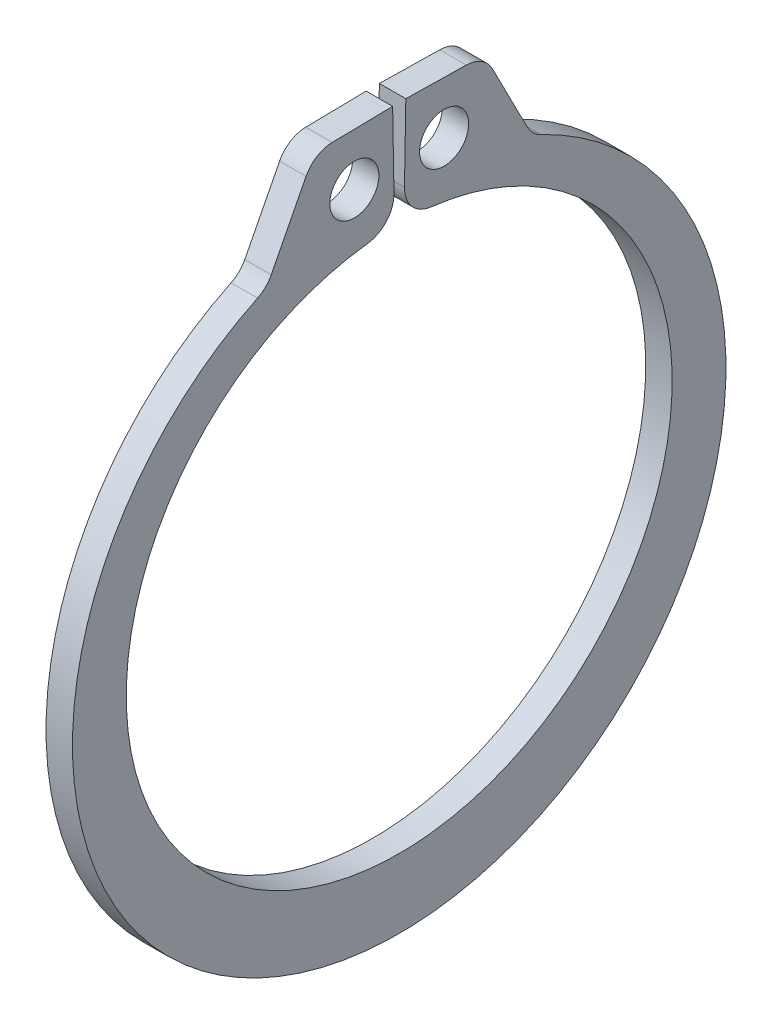
SolidWorks part; units mm, degrees
material "Cast Carbon Steel"
ref_plane "Front" through (0, 0, 0) normal (0, 0, 1) x (1, 0, 0)
ref_plane "Top" through (0, 0, 0) normal (0, 1, 0) x (1, 0, 0)
ref_plane "Right" through (0, 0, 0) normal (1, 0, 0) x (0, 0, -1)
sketch "Sketch1" plane through (0, 0, 0) normal (1, 0, 0) x (0, 0, -1)
  line L0 (0, 0) -> (0, 11.0109) construction
  line L1 (-0.1922, 11.0092) -> (-0.2658, 15.225)
  line L2 (0.2658, 15.225) -> (3.4276, 15.1698)
  line L3 (3.4276, 15.1698) -> (5.3529, 11.4187)
  line L4 (0.1922, 11.0092) -> (0.2658, 15.225)
  line L5 (-0.2658, 15.225) -> (-3.4276, 15.1698)
  line L6 (-3.4276, 15.1698) -> (-5.3529, 11.4187)
  line L7 (-5.3529, 11.4187) -> (-4.6737, 9.9698) construction
  line L8 (5.3529, 11.4187) -> (4.6737, 9.9698) construction
  line L9 (0, -11.0109) -> (0, -13.8049) construction
  line L10 (-3.4276, 15.1698) -> (-0.1922, 11.0092) construction
  line L11 (0, 11.0109) -> (0, 15.2273) construction
  line L12 (-11.0109, 0) -> (11.0109, 0) construction
  circle A0 centre (0, 0) radius 11.0109 construction
  arc A1 (-0.1922, 11.0092) -> (0.1922, 11.0092) centre (0, 0) ccw
  circle A4 centre (-1.8099, 13.0895) radius 0.9906
  circle A5 centre (1.8099, 13.0895) radius 0.9906
  arc A6 (-5.3529, 11.4187) -> (5.3529, 11.4187) centre (0, -0.6251) ccw construction
  point P0 (0, -13.8049)
  dimension "Ring ID" = 22.0218
  dimension "Hole Diameter" = 1.9812
  dimension "Min. Sec." = 1.6002
  dimension "Max. Sec." = 2.794
  dimension "Lug Height" = 4.2164
  dimension "D2" = 3.1623
  dimension "Angle" = 1
sketch "Sketch2" plane through (0, 0, 0) normal (0, 1, 0) x (1, 0, 0)
  line L0 (-0.5334, -13.1649) -> (0.5334, -13.1649) construction
  line L1 (0, -13.1798) -> (0, 13.1798) construction
  point P8 (0, -13.1649)
  dimension "Ring Thickness" = 1.0668
sketch "Sketch3" plane through (0, 0, 0) normal (1, 0, 0) x (0, 0, -1)
  line L0 (-3.4276, 15.1698) -> (-5.3529, 11.4187) construction
  line L1 (-3.4276, 15.1698) -> (-5.3529, 11.4187)
  line L2 (-0.2658, 15.225) -> (-3.4276, 15.1698) construction
  line L3 (-0.2658, 15.225) -> (-3.4276, 15.1698)
  line L4 (-0.1922, 11.0092) -> (-0.2658, 15.225) construction
  line L5 (-0.1922, 11.0092) -> (-0.2658, 15.225)
  line L6 (0.1922, 11.0092) -> (0.2658, 15.225) construction
  line L7 (0.1922, 11.0092) -> (0.2658, 15.225)
  line L8 (0.2658, 15.225) -> (3.4276, 15.1698) construction
  line L9 (0.2658, 15.225) -> (3.4276, 15.1698)
  line L10 (3.4276, 15.1698) -> (5.3529, 11.4187) construction
  line L11 (3.4276, 15.1698) -> (5.3529, 11.4187)
  arc A0 (-5.3529, 11.4187) -> (5.3529, 11.4187) centre (0, -0.6251) ccw construction
  arc A1 (-5.3529, 11.4187) -> (5.3529, 11.4187) centre (0, -0.6251) ccw
  arc A2 (-0.1922, 11.0092) -> (0.1922, 11.0092) centre (0, 0) ccw construction
  arc A3 (-0.1922, 11.0092) -> (0.1922, 11.0092) centre (0, 0) ccw
  circle A4 centre (-1.8099, 13.0895) radius 0.9906 construction
  circle A5 centre (-1.8099, 13.0895) radius 0.9906
  circle A6 centre (1.8099, 13.0895) radius 0.9906 construction
  circle A7 centre (1.8099, 13.0895) radius 0.9906
extrude "Boss-Extrude1" add sketch "Sketch3" along normal up to vertex (0.5334 mm away) and the other way up to vertex (0.5334 mm away) up to point (0.5334, 0, 13.1649) other way up to point (-0.5334, 0, 13.1649)
fillet "Fillet1" radius 1.2065 6 edges at (0, 11.4187, -5.3529) (0, 15.1698, -3.4276) (0, 11.0092, -0.1922) (0, 11.0092, 0.1922) (0, 15.1698, 3.4276) (0, 11.4187, 5.3529)
sketch "Sketch4" plane through (0, 0, 0) normal (1, 0, 0) x (0, 0, -1)
  line L0 (-9.5357, 5.5055) -> (0, 0) construction
  line L1 (0, 0) -> (0, 11.0109) construction
  line L2 (0, 15.2273) -> (0, 11.0109) construction
  arc A0 (-0.1922, 11.0092) -> (0.1922, 11.0092) centre (0, 0) ccw construction
  point P0 (0, 0)
  point P1 (-9.5357, 5.5055)
  dimension "D1" = 60
equation "\"D2@Sketch1\" = \"Lug Height@Sketch1\" * .75"
